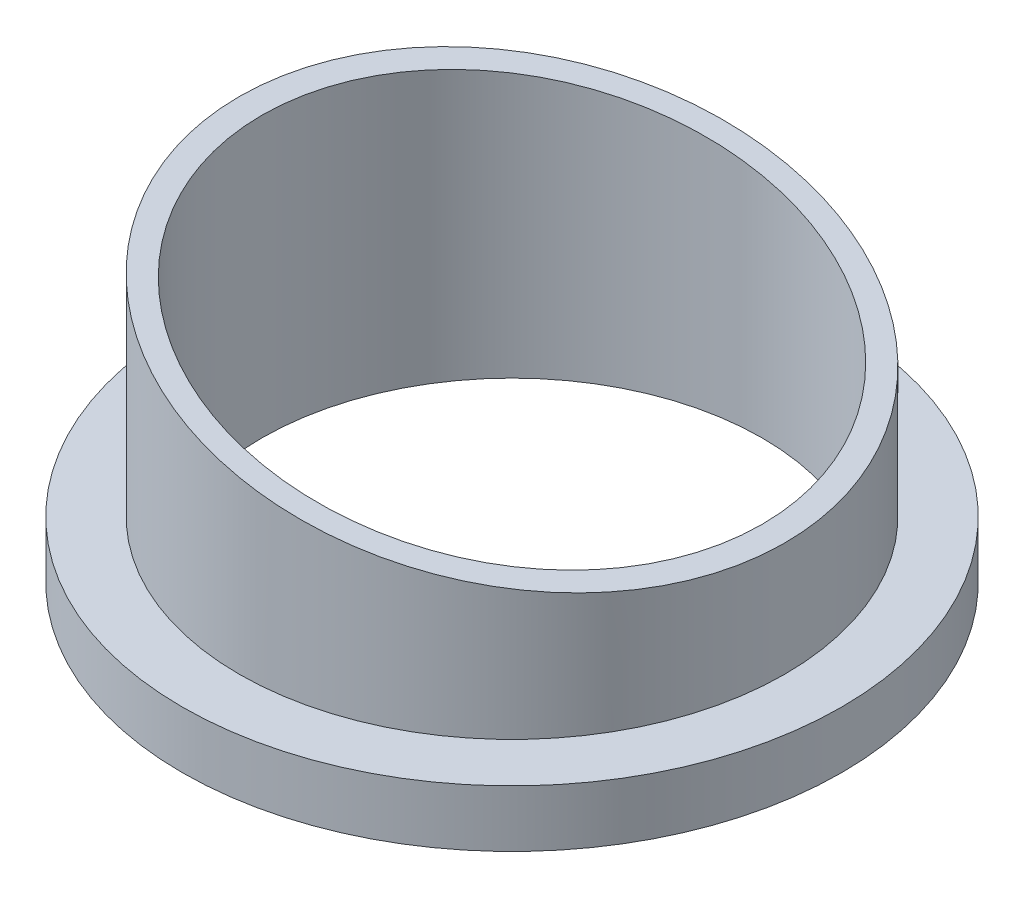
SolidWorks part; units mm, degrees
ref_plane "Front" through (0, 0, 0) normal (0, 0, 1) x (1, 0, 0)
ref_plane "Top" through (0, 0, 0) normal (0, 1, 0) x (1, 0, 0)
ref_plane "Right" through (0, 0, 0) normal (1, 0, 0) x (0, 0, -1)
sketch "Sketch1" plane through (0, 0, 0) normal (0, 1, 0) x (1, 0, 0)
  circle A0 centre (0, 0) radius 14.5
  dimension "D1" = 29
extrude "Boss-Extrude1" add sketch "Sketch1" along normal blind 12.5
sketch "Sketch2" plane through (0, 12.5, 0) normal (0, 1, 0) x (1, 0, 0)
  circle A0 centre (0, 0) radius 12
  circle A2 centre (0, 0) radius 14.5
  circle A3 centre (0, 0) radius 14.5 construction
  dimension "D1" = 2.5
extrude "Cut-Extrude1" cut sketch "Sketch2" against normal blind 10
sketch "Sketch4" plane through (0, 12.5, 0) normal (0, 1, 0) x (1, 0, 0)
  circle A0 centre (0, 0) radius 11
  dimension "D1" = 22
extrude "Cut-Extrude2" cut sketch "Sketch4" against normal through all
sketch "Sketch5" plane through (0, 0, 0) normal (0, 0, 1) x (1, 0, 0)
  line L6 (-12, 12.5) -> (12, 12.5)
  line L8 (12, 12.5) -> (12, 7.5)
  line L9 (12, 2.5) -> (12, 12.5) construction
  line L10 (12, 7.5) -> (-12, 12.5)
extrude "Cut-Extrude3" cut sketch "Sketch5" against normal through all both and the other way through all
